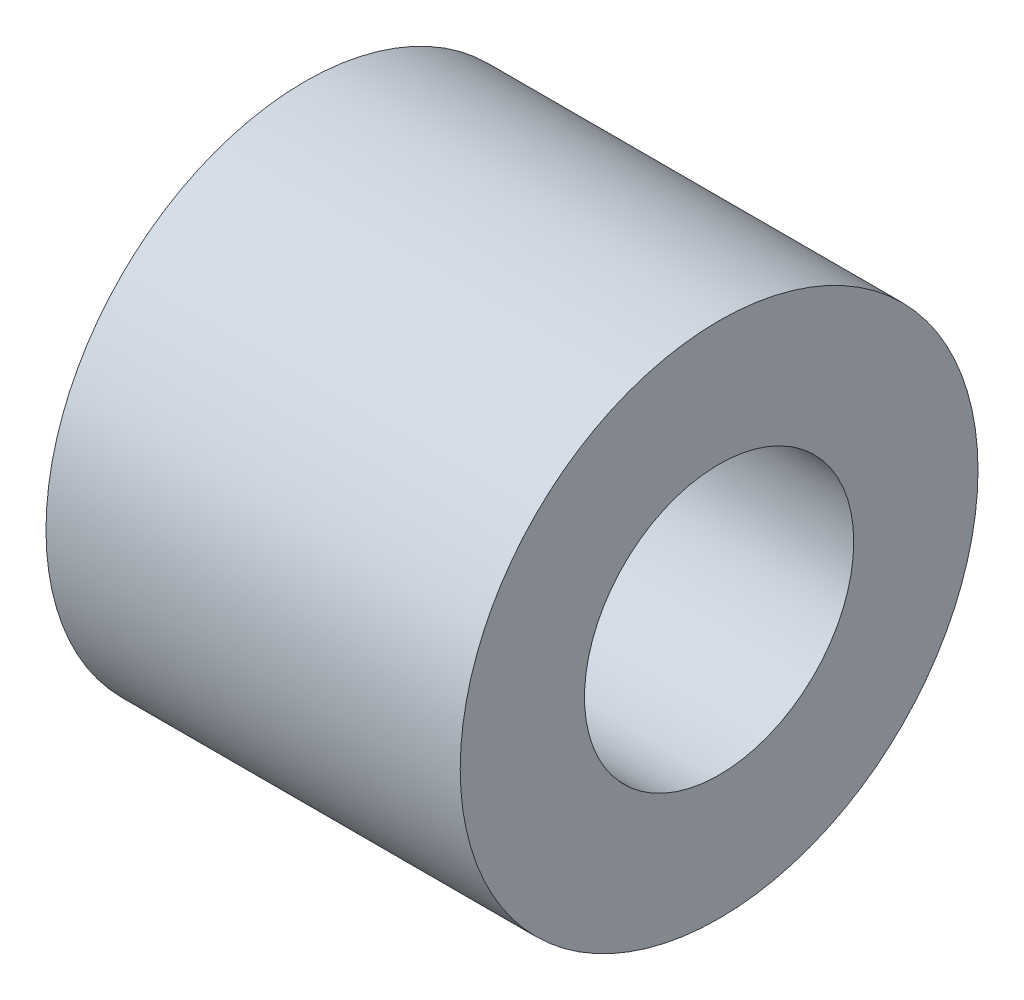
SolidWorks part; units mm, degrees
ref_plane "Front Plane" through (0, 0, 0) normal (0, 0, 1) x (1, 0, 0)
ref_plane "Top Plane" through (0, 0, 0) normal (0, 1, 0) x (1, 0, 0)
ref_plane "Right Plane" through (0, 0, 0) normal (1, 0, 0) x (0, 0, -1)
sketch "Sketch1" plane through (0, 0, 0) normal (1, 0, 0) x (0, 0, -1)
  circle A0 centre (0, 0) radius 6.35
  circle A1 centre (0, 0) radius 3.302
  dimension "D1" = 6.604
  dimension "D2" = 12.7
extrude "Boss-Extrude1" add sketch "Sketch1" along normal blind 10.16
